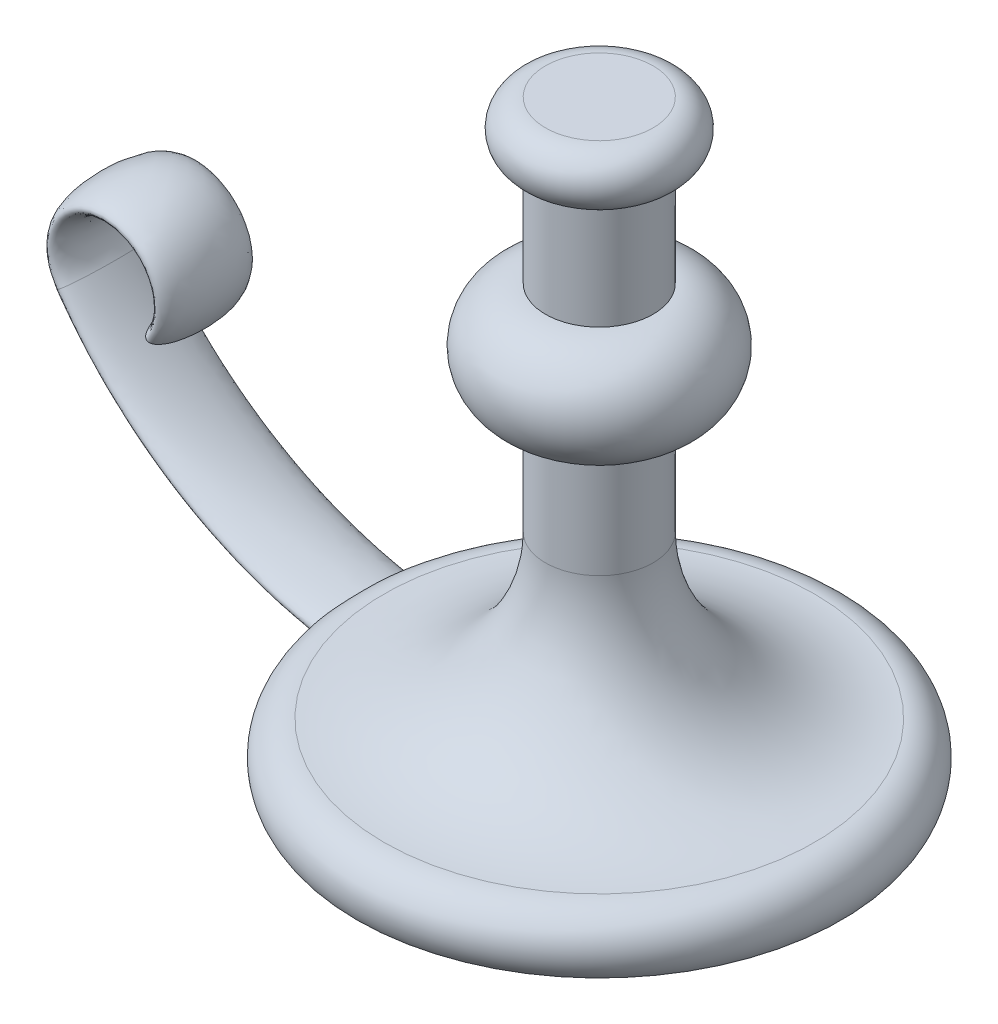
SolidWorks part; units mm, degrees
ref_plane "Front Plane" through (0, 0, 0) normal (0, 0, 1) x (1, 0, 0)
ref_plane "Top Plane" through (0, 0, 0) normal (0, 1, 0) x (1, 0, 0)
ref_plane "Right Plane" through (0, 0, 0) normal (1, 0, 0) x (0, 0, -1)
sketch "Sketch1" plane through (0, 0, 0) normal (0, 0, 1) x (1, 0, 0)
  line L0 (0, 0) -> (90, 0)
  line L1 (0, 0) -> (0, 220)
  line L2 (0, 220) -> (20, 220)
  line L3 (20, 200) -> (20, 160)
  line L4 (20, 120) -> (20, 80)
  arc A0 (20, 220) -> (20, 200) centre (20, 210) cw
  arc A1 (20, 160) -> (20, 120) centre (20, 140) cw
  arc A2 (20, 80) -> (80, 20) centre (80, 80) ccw
  arc A3 (80, 20) -> (90, 0) centre (80, 7.5) cw
  dimension "D4" = 10
  dimension "D6" = 20
  dimension "D8" = 60
  dimension "D9" = 12.5
  dimension "D1" = 20
  dimension "D2" = 220
  dimension "D3" = 90
  dimension "D5" = 80
  dimension "D7" = 40
revolve "Revolve1" add sketch "Sketch1" angle 360 about L1
sketch "Sketch2" plane through (0, 0, 0) normal (0, 0, 1) x (1, 0, 0)
  line L0 (0, 10) -> (-60, 10)
  line L1 (0, 200) -> (0, 160) construction
  line L2 (0, 227.4356) -> (0, 175.1288) construction
  line L3 (-90, 0) -> (90, 0) construction
  arc A0 (-60, 10) -> (-183.5921, 75) centre (-60, 160) cw
  arc A1 (-183.5921, 75) -> (-150.6342, 75) centre (-167.1131, 86.3333) cw
  point P10 (0, 0)
  dimension "D3" = 150
  dimension "D4" = 20
  dimension "D1" = 60
  dimension "D2" = 65
  dimension "D5" = 10
sketch "Sketch3" plane through (0, 0, 0) normal (1, 0, 0) x (0, 0, -1)
  ellipse E0 centre (0, 10) end of major axis (17.5, 10) minor radius 5
  dimension "D1" = 35
  dimension "D2" = 10
sweep "Sweep1" add profiles "Sketch3" path "Sketch2"
